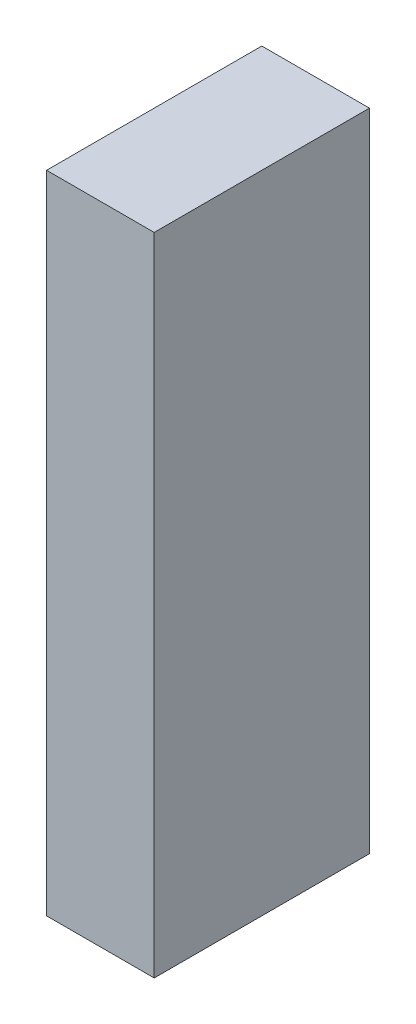
SolidWorks part; units mm, degrees
ref_plane "Plan de face" through (0, 0, 0) normal (0, 0, 1) x (1, 0, 0)
ref_plane "Plan de dessus" through (0, 0, 0) normal (0, 1, 0) x (1, 0, 0)
ref_plane "Plan de droite" through (0, 0, 0) normal (1, 0, 0) x (0, 0, -1)
sketch "Esquisse2" plane through (0, 0, 0) normal (0, 1, 0) x (1, 0, 0)
  line L1 (0, 0) -> (50.8, 0)
  line L2 (0, 0) -> (0, 101.6)
  line L3 (0, 101.6) -> (50.8, 101.6)
  line L4 (50.8, 0) -> (50.8, 101.6)
  dimension "D1" = 101.6
  dimension "D2" = 50.8
extrude "Boss.-Extru.2" add sketch "Esquisse2" along normal blind 304.8
